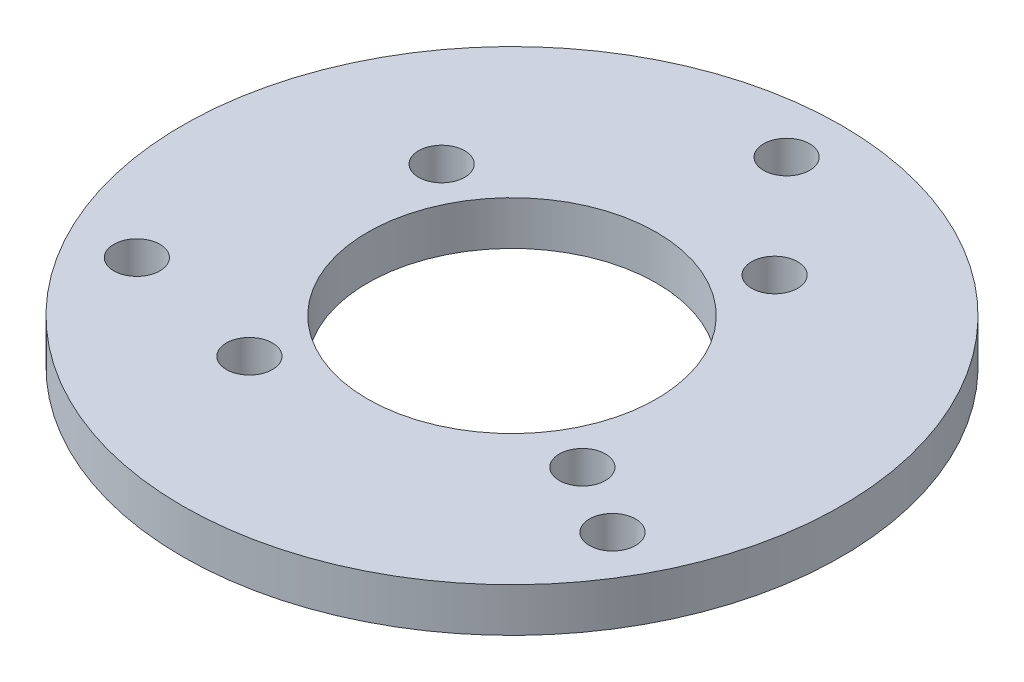
SolidWorks part; units mm, degrees
material "1060 合金"
ref_plane "前视基准面" through (0, 0, 0) normal (0, 0, 1) x (1, 0, 0)
ref_plane "上视基准面" through (0, 0, 0) normal (0, 1, 0) x (1, 0, 0)
ref_plane "右视基准面" through (0, 0, 0) normal (1, 0, 0) x (0, 0, -1)
sketch "草图1" plane through (0, 0, 0) normal (0, 1, 0) x (1, 0, 0)
  circle A0 centre (0, 0) radius 30
  dimension "D1" = 60
extrude "凸台-拉伸1" add sketch "草图1" along normal blind 4
sketch "草图2" plane through (0, 4, 0) normal (0, 1, 0) x (1, 0, 0)
  circle A0 centre (0, 0) radius 25
  circle A1 centre (0, 25) radius 2.1
  dimension "D1" = 50
  dimension "D2" = 4.2
extrude "切除-拉伸1" cut sketch "草图2" against normal blind 4 contours A0 A1 | A0 A1
pattern_circular "阵列(圆周)1" count 3 over 360 about axis through (0, 0, 0) along (0, 1, 0) of "切除-拉伸1"
sketch "草图3" plane through (0, 4, 0) normal (0, 1, 0) x (1, 0, 0)
  circle A0 centre (0, 0) radius 13.15
  dimension "D1" = 26.3
extrude "切除-拉伸2" cut sketch "草图3" against normal blind 17
sketch "草图4" plane through (0, 4, 0) normal (0, 1, 0) x (1, 0, 0)
  line L0 (0, 0) -> (21.6506, -12.5)
  circle A0 centre (0, 0) radius 17.5
  circle A1 centre (15.1554, -8.75) radius 2.1
  dimension "D1" = 35
  dimension "D2" = 4.2
  dimension "D3" = 0
extrude "切除-拉伸3" cut sketch "草图4" against normal blind 17 contours L0 A1 A0 | A0 A1 L0 | L0 A1 A0 | A0 A1 L0
pattern_circular "阵列(圆周)2" count 4 over 360 about axis through (0, 0, 0) along (0, 1, 0) of "切除-拉伸3"
